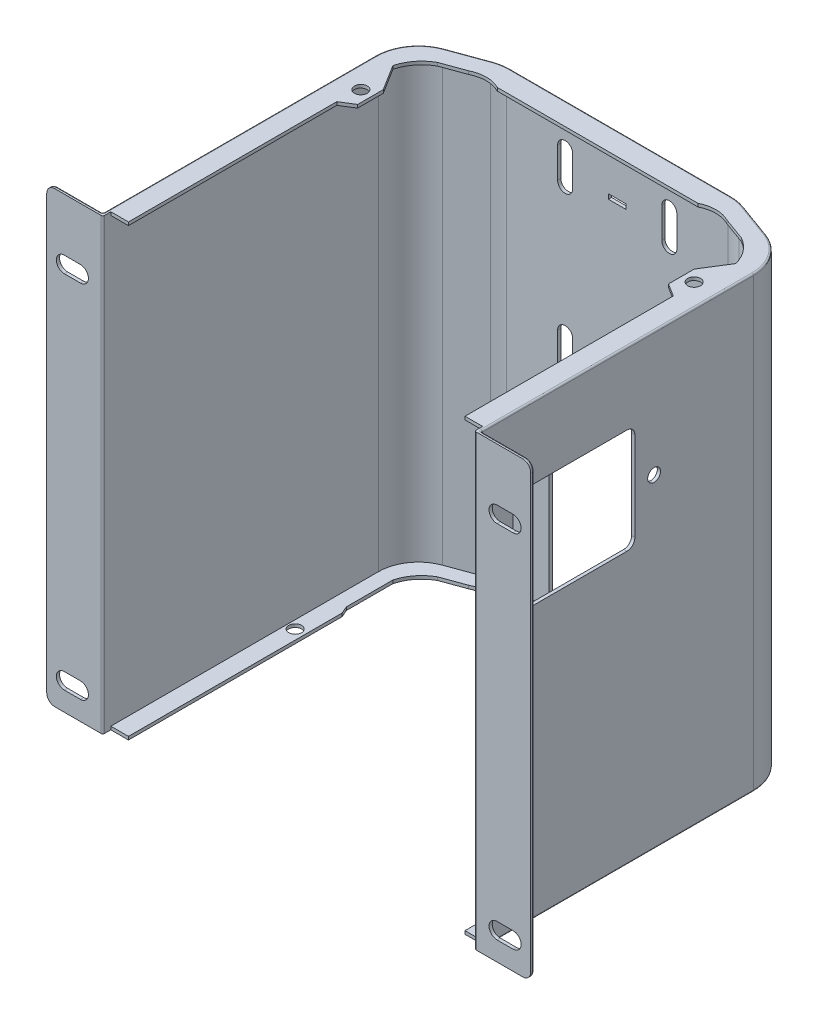
SolidWorks part; units mm, degrees
ref_plane "Front Plane" through (0, 0, 0) normal (0, 0, 1) x (1, 0, 0)
ref_plane "Top Plane" through (0, 0, 0) normal (0, 1, 0) x (1, 0, 0)
ref_plane "Right Plane" through (0, 0, 0) normal (1, 0, 0) x (0, 0, -1)
sketch "Sketch1" plane through (0, 0, 0) normal (0, 1, 0) x (1, 0, 0)
  line L0 (-72.524, 103.4923) -> (-94.5505, 95.4753)
  line L1 (-63.9735, 105) -> (73.9735, 105)
  line L2 (-111, 71.983) -> (-111, -99)
  line L4 (121, 71.983) -> (121, -99)
  line L5 (-109.326, 90.3521) -> (121, -100) construction
  line L6 (-111, -100) -> (111, 100) construction
  line L7 (82.524, 103.4923) -> (104.5505, 95.4753)
  line L8 (122, -100) -> (156, -100)
  line L9 (-112, -100) -> (-146, -100)
  line L10 (-114, -98) -> (-146, -98)
  line L11 (-113, 71.983) -> (-113, -97)
  line L12 (-73.208, 105.3717) -> (-95.2345, 97.3547)
  line L13 (-63.9735, 107) -> (73.9735, 107)
  line L14 (83.208, 105.3717) -> (105.2345, 97.3547)
  line L15 (123, 71.983) -> (123, -97)
  line L16 (124, -98) -> (156, -98)
  line L17 (-146, -98) -> (-146, -100)
  line L18 (156, -98) -> (156, -100)
  line L19 (-113, -98) -> (-146, -98) construction
  line L20 (-113, 71.983) -> (-113, -98) construction
  line L21 (-111, -100) -> (-146, -100) construction
  line L22 (-111, 71.983) -> (-111, -100) construction
  line L23 (123, -98) -> (156, -98) construction
  line L24 (123, 71.983) -> (123, -98) construction
  line L25 (121, -100) -> (156, -100) construction
  line L26 (121, 71.983) -> (121, -100) construction
  arc A0 (121, 71.983) -> (104.5505, 95.4753) centre (96, 71.983) ccw
  arc A1 (-111, 71.983) -> (-94.5505, 95.4753) centre (-86, 71.983) cw
  arc A2 (82.524, 103.4923) -> (73.9735, 105) centre (73.9735, 80) ccw
  arc A3 (-72.524, 103.4923) -> (-63.9735, 105) centre (-63.9735, 80) cw
  arc A4 (-113, 71.983) -> (-95.2345, 97.3547) centre (-86, 71.983) cw
  arc A5 (-73.208, 105.3717) -> (-63.9735, 107) centre (-63.9735, 80) cw
  arc A6 (83.208, 105.3717) -> (73.9735, 107) centre (73.9735, 80) ccw
  arc A7 (123, 71.983) -> (105.2345, 97.3547) centre (96, 71.983) ccw
  arc A8 (-114, -98) -> (-113, -97) centre (-114, -97) ccw
  arc A9 (-112, -100) -> (-111, -99) centre (-112, -99) ccw
  arc A10 (124, -98) -> (123, -97) centre (124, -97) cw
  arc A11 (122, -100) -> (121, -99) centre (122, -99) cw
  point P0 (0, 0)
  dimension "D1" = 25
  dimension "D2" = 25
  dimension "D8" = 1
  dimension "D3" = 35
  dimension "D4" = 35
  dimension "D5" = 20
  dimension "D6" = 20
  dimension "D7" = 2
extrude "Boss-Extrude1" add sketch "Sketch1" against normal blind 280
fillet "Fillet1" radius 5 4 edges at (156, 0, 99) (-146, 0, 99) (-146, -280, 99) (156, -280, 99)
sketch "Sketch2" plane through (0, -280, 0) normal (0, -1, 0) x (1, 0, 0)
  line L0 (-102, -47.983) -> (-102, -55.983)
  line L1 (5, -106) -> (5, -85.9828) construction
  line L2 (99.7633, -87.6401) -> (85.6679, -92.7704)
  line L3 (112, -55.983) -> (112, -71.983)
  line L4 (112, -47.983) -> (112, -55.983)
  line L5 (112, -42.983) -> (112, -47.983)
  line L6 (110, -38.3496) -> (112, -42.983)
  line L7 (110, 95) -> (110, -38.3496)
  line L8 (122, 95) -> (110, 95)
  line L25 (-112, 95) -> (-100, 95)
  line L26 (-100, 95) -> (-100, -38.3496)
  line L27 (-100, -38.3496) -> (-102, -42.983)
  line L28 (-102, -42.983) -> (-102, -47.983)
  line L30 (-102, -55.983) -> (-102, -71.983)
  line L31 (-89.7633, -87.6401) -> (-75.6679, -92.7704)
  line L32 (-57.5976, -92.7704) -> (67.5976, -92.7704)
  line L33 (-141, 100) -> (-112, 100) construction
  line L34 (-141, 99) -> (-146, 99)
  line L35 (156, 99) -> (151, 99)
  line L36 (151, 99) -> (122, 99)
  line L37 (122, 99) -> (122, -71.983)
  line L38 (104.8925, -96.415) -> (82.866, -104.432)
  line L39 (73.9735, -106) -> (-63.9735, -106)
  line L40 (-72.866, -104.432) -> (-94.8925, -96.415)
  line L41 (-112, 99) -> (-141, 99)
  line L42 (-112, -71.983) -> (-112, 99)
  line L44 (156, 99) -> (151, 99)
  line L45 (151, 99) -> (122, 99)
  line L46 (122, 99) -> (122, -71.983)
  line L47 (104.8925, -96.415) -> (82.866, -104.432)
  line L48 (73.9735, -106) -> (-63.9735, -106)
  line L49 (-72.866, -104.432) -> (-94.8925, -96.415)
  line L51 (-112, -71.983) -> (-112, 95)
  arc A0 (85.6679, -92.7704) -> (67.5976, -92.7704) centre (76.6328, -74.9276) cw
  arc A1 (112, -71.983) -> (99.7633, -87.6401) centre (87.8063, -65.6849) cw
  circle A2 centre (-106, -15) radius 4
  circle A3 centre (116, -15) radius 4
  arc A18 (-102, -71.983) -> (-89.7633, -87.6401) centre (-77.8063, -65.6849) ccw
  arc A19 (-75.6679, -92.7704) -> (-57.5976, -92.7704) centre (-66.6328, -74.9276) ccw
  arc A24 (104.8925, -96.415) -> (122, -71.983) centre (96, -71.983) ccw
  arc A25 (73.9735, -106) -> (82.866, -104.432) centre (73.9735, -80) ccw
  arc A26 (-72.866, -104.432) -> (-63.9735, -106) centre (-63.9735, -80) ccw
  arc A27 (-112, -71.983) -> (-94.8925, -96.415) centre (-86, -71.983) ccw
  arc A28 (104.8925, -96.415) -> (122, -71.983) centre (96, -71.983) ccw
  arc A29 (73.9735, -106) -> (82.866, -104.432) centre (73.9735, -80) ccw
  arc A30 (-72.866, -104.432) -> (-63.9735, -106) centre (-63.9735, -80) ccw
  arc A31 (-112, -71.983) -> (-94.8925, -96.415) centre (-86, -71.983) ccw
  line M42 (121, 99) -> (121, -71.983)
  arc M43 (121, -71.983) -> (104.5505, -95.4753) centre (96, -71.983) cw
  line M44 (104.5505, -95.4753) -> (82.524, -103.4923)
  arc M45 (82.524, -103.4923) -> (73.9735, -105) centre (73.9735, -80) cw
  line M46 (73.9735, -105) -> (-63.9735, -105)
  arc M47 (-63.9735, -105) -> (-72.524, -103.4923) centre (-63.9735, -80) cw
  line M48 (-72.524, -103.4923) -> (-94.5505, -95.4753)
  arc M49 (-94.5505, -95.4753) -> (-111, -71.983) centre (-86, -71.983) cw
  line M50 (-111, -71.983) -> (-111, 99)
  dimension "D5" = 10
  dimension "D6" = 25
  dimension "D7" = 20
  dimension "D11" = 8
  dimension "D12" = 110
  dimension "D13" = 6
  dimension "D2" = 5
  dimension "D3" = 12
  dimension "D4" = 10
  dimension "D8" = 5
  dimension "D9" = 8
  dimension "D10" = 16
  dimension "D14" = 15
  dimension "D15" = 10
  dimension "D1" = 1
extrude "Boss-Extrude2" add sketch "Sketch2" against normal blind 2 contours L1 L8 L7 L6 L5 L4 L3 A1 L2 A0 L32 A3 M46 M45 M44 M43 M42 | L1 L32 A19 L31 A18 L30 L0 L28 L27 L26 L25 A2 M46 M50 M49 M48 M47
ref_plane "Plane1" through (0, -140, 0) normal (0, 1, 0) x (1, 0, 0)
sketch "Sketch3" plane through (0, 0, 0) normal (0, 1, 0) x (1, 0, 0)
  line L0 (5, 92.7704) -> (5, 63.9915) construction
  line L1 (122, -95) -> (110, -95)
  line L2 (110, -95) -> (110, 35)
  line L3 (110, 35) -> (102, 40)
  line L4 (102, 40) -> (102, 56)
  line L5 (102, 56) -> (112, 71.983)
  line L6 (99.7633, 87.6401) -> (85.6679, 92.7704)
  line L14 (-112, -95) -> (-100, -95)
  line L15 (-100, -95) -> (-100, 35)
  line L16 (-100, 35) -> (-92, 40)
  line L17 (-92, 40) -> (-92, 56)
  line L18 (-92, 56) -> (-102, 71.983)
  line L19 (122, 71.983) -> (122, -99)
  line L20 (82.866, 104.432) -> (104.8925, 96.415)
  line L21 (-112, -99) -> (-112, 71.983)
  line L22 (-63.9735, 106) -> (73.9735, 106)
  line L23 (-94.8925, 96.415) -> (-72.866, 104.432)
  line L24 (122, 71.983) -> (122, -95)
  line L25 (82.866, 104.432) -> (104.8925, 96.415)
  line L26 (-112, -95) -> (-112, 71.983)
  line L27 (-63.9735, 106) -> (73.9735, 106)
  line L28 (-94.8925, 96.415) -> (-72.866, 104.432)
  line L30 (-89.7633, 87.6401) -> (-75.6679, 92.7704)
  line L31 (-141, -100) -> (-112, -100) construction
  line L32 (-57.5976, 92.7704) -> (67.5976, 92.7704)
  circle A0 centre (109, 49) radius 4
  arc A1 (112, 71.983) -> (99.7633, 87.6401) centre (87.8063, 65.6849) ccw
  arc A2 (85.6679, 92.7704) -> (67.5976, 92.7704) centre (76.6328, 74.9276) ccw
  arc A10 (-102, 71.983) -> (-89.7633, 87.6401) centre (-77.8063, 65.6849) cw
  arc A11 (-75.6679, 92.7704) -> (-57.5976, 92.7704) centre (-66.6328, 74.9276) cw
  arc A14 (122, 71.983) -> (104.8925, 96.415) centre (96, 71.983) ccw
  arc A15 (82.866, 104.432) -> (73.9735, 106) centre (73.9735, 80) ccw
  arc A16 (-63.9735, 106) -> (-72.866, 104.432) centre (-63.9735, 80) ccw
  arc A17 (-94.8925, 96.415) -> (-112, 71.983) centre (-86, 71.983) ccw
  arc A18 (122, 71.983) -> (104.8925, 96.415) centre (96, 71.983) ccw
  arc A19 (82.866, 104.432) -> (73.9735, 106) centre (73.9735, 80) ccw
  arc A20 (-63.9735, 106) -> (-72.866, 104.432) centre (-63.9735, 80) ccw
  arc A21 (-94.8925, 96.415) -> (-112, 71.983) centre (-86, 71.983) ccw
  circle A22 centre (-99, 49) radius 4
  point P31 (82.7156, 90.2053)
  dimension "D8" = 144
  dimension "D9" = 7
  dimension "D10" = 8
  dimension "D2" = 12
  dimension "D3" = 5
  dimension "D4" = 20
  dimension "D5" = 16
  dimension "D6" = 5
  dimension "D7" = 130
  dimension "D1" = 1
extrude "Boss-Extrude3" add sketch "Sketch3" against normal blind 2
fillet "Fillet3" radius 1 32 edges at (-84.2213, 0, -101.3632) (-68.662, 0, -106.5898) (5, 0, -107) (78.662, 0, -106.5898) (94.2213, 0, -101.3632) (118.1171, 0, -87.4696) (123, 0, 12.5085) (123.2929, 0, 97.7071) (137.5, 0, 98) (154.5355, -1.4645, 98) (156, -140, 98) (154.5355, -278.5355, 98) (137.5, -280, 98) (123.2929, -280, 97.7071) (123, -280, 12.5085) (118.1171, -280, -87.4696) (94.2213, -280, -101.3632) (78.662, -280, -106.5898) (5, -280, -107) (-68.662, -280, -106.5898) (-84.2213, -280, -101.3632) (-108.1171, 0, -87.4696) (-108.1171, -280, -87.4696) (-113, 0, 12.5085) (-113, -280, 12.5085) (-113.2929, 0, 97.7071) (-113.2929, -280, 97.7071) (-127.5, -280, 98) (-144.5355, -278.5355, 98) (-146, -140, 98) (-144.5355, -1.4645, 98) (-127.5, 0, 98)
sketch "Sketch6" plane through (0, 0, 98) normal (0, 0, -1) x (-1, 0, 0)
  line L0 (125, -38) -> (135, -38) construction
  line L1 (125, -33) -> (135, -33)
  line L2 (125, -43) -> (135, -43)
  line L3 (145, -275) -> (145, -5) construction
  line L4 (141, -1) -> (114, -1) construction
  line L5 (125, -263) -> (135, -263) construction
  line L6 (125, -258) -> (135, -258)
  line L7 (125, -268) -> (135, -268)
  line L8 (-5, -1) -> (-5, 16.278) construction
  line L9 (141, -1) -> (-151, -1) construction
  line L10 (-135, -38) -> (-145, -38) construction
  line L11 (-135, -33) -> (-145, -33)
  line L12 (-135, -43) -> (-145, -43)
  line L13 (-135, -263) -> (-145, -263) construction
  line L14 (-135, -258) -> (-145, -258)
  line L15 (-135, -268) -> (-145, -268)
  arc A0 (125, -33) -> (125, -43) centre (125, -38) ccw
  arc A1 (135, -43) -> (135, -33) centre (135, -38) ccw
  arc A2 (125, -258) -> (125, -268) centre (125, -263) ccw
  arc A3 (135, -268) -> (135, -258) centre (135, -263) ccw
  arc A4 (-135, -33) -> (-135, -43) centre (-135, -38) cw
  arc A5 (-145, -43) -> (-145, -33) centre (-145, -38) cw
  arc A6 (-135, -258) -> (-135, -268) centre (-135, -263) cw
  arc A7 (-145, -268) -> (-145, -258) centre (-145, -263) cw
  point P2 (130, -38)
  point P13 (130, -263)
  point P27 (-140, -38)
  point P34 (-140, -263)
  dimension "D1" = 5
  dimension "D3" = 10
  dimension "D5" = 5
  dimension "D7" = 10
  dimension "D2" = 10
  dimension "D4" = 32
  dimension "D6" = 10
  dimension "D8" = 215
extrude "Cut-Extrude3" cut sketch "Sketch6" along direction (0, 0, 1) on the side against the normal up to surface (2 mm away) contours L2 A1 L1 A0 | L7 A3 L6 A2 | A7 L15 A6 L14 | A5 L12 A4 L11
sketch "Sketch7" plane through (0, 0, -107) normal (0, 0, -1) x (-1, 0, 0)
  line L0 (-37.5, -24.5033) -> (-37.5, -43.5682) construction
  line L1 (-32.7898, -24.5033) -> (-32.7898, -43.5682)
  line L2 (-42.2102, -24.5033) -> (-42.2102, -43.5682)
  line L3 (27.5, -24.5033) -> (27.5, -43.5682) construction
  line L4 (32.2102, -24.5033) -> (32.2102, -43.5682)
  line L5 (22.7898, -24.5033) -> (22.7898, -43.5682)
  line L6 (27.5, -124.5033) -> (27.5, -143.5682) construction
  line L7 (32.2102, -124.5033) -> (32.2102, -143.5682)
  line L8 (22.7898, -124.5033) -> (22.7898, -143.5682)
  line L9 (-37.5, -124.5033) -> (-37.5, -143.5682) construction
  line L10 (-32.7898, -124.5033) -> (-32.7898, -143.5682)
  line L11 (-42.2102, -124.5033) -> (-42.2102, -143.5682)
  line L12 (-5, -1) -> (-5, -16.0632) construction
  line L13 (63.9735, -1) -> (-73.9735, -1) construction
  line L14 (-73.9735, -279) -> (63.9735, -279) construction
  line L15 (37.5, -376.5) -> (-47.5, -376.5)
  line L16 (37.5, -376.5) -> (37.5, -181.5)
  line L18 (-47.5, -376.5) -> (-47.5, -181.5)
  line L19 (37.5, -376.5) -> (-47.5, -181.5) construction
  line L20 (37.5, -181.5) -> (-47.5, -376.5) construction
  arc A0 (-32.7898, -24.5033) -> (-42.2102, -24.5033) centre (-37.5, -24.5033) ccw
  arc A1 (-42.2102, -43.5682) -> (-32.7898, -43.5682) centre (-37.5, -43.5682) ccw
  arc A2 (32.2102, -24.5033) -> (22.7898, -24.5033) centre (27.5, -24.5033) ccw
  arc A3 (22.7898, -43.5682) -> (32.2102, -43.5682) centre (27.5, -43.5682) ccw
  arc A4 (32.2102, -124.5033) -> (22.7898, -124.5033) centre (27.5, -124.5033) ccw
  arc A5 (22.7898, -143.5682) -> (32.2102, -143.5682) centre (27.5, -143.5682) ccw
  arc A6 (-32.7898, -124.5033) -> (-42.2102, -124.5033) centre (-37.5, -124.5033) ccw
  arc A7 (-42.2102, -143.5682) -> (-32.7898, -143.5682) centre (-37.5, -143.5682) ccw
  arc A8 (-47.5, -181.5) -> (37.5, -181.5) centre (-5, -181.5) cw
  point P2 (-37.5, -34.0358)
  point P12 (27.5, -34.0358)
  point P19 (27.5, -134.0358)
  point P26 (-37.5, -134.0358)
  point P32 (-5, -279)
  dimension "D3" = 32.5
  dimension "D4" = 85
  dimension "D1" = 2
  dimension "D2" = 2
extrude "Cut-Extrude4" cut sketch "Sketch7" against normal through all
sketch "Sketch8" plane through (0, 0, -107) normal (0, 0, -1) x (-1, 0, 0)
  line L1 (-10.5, -35) -> (0.5, -35)
  line L2 (-10.5, -35) -> (-10.5, -38)
  line L3 (-10.5, -38) -> (0.5, -38)
  line L4 (0.5, -35) -> (0.5, -38)
  line L5 (-73.9735, -1) -> (63.9735, -1) construction
  point P4 (-5, -35)
  point P10 (-5, -1)
  dimension "D1" = 11
  dimension "D2" = 3
  dimension "D3" = 35
extrude "Cut-Extrude5" cut sketch "Sketch8" against normal up to surface (2 mm away) up to face at (-27.5, -34.0358, -105)
sketch "Sketch9" plane through (123, 0, 0) normal (1, 0, 0) x (0, 0, -1)
  line L0 (-98, -5) -> (-98, -275) construction
  line L1 (-78, -45) -> (-2, -45)
  line L2 (-78, -45) -> (-78, -110.5)
  line L3 (-78, -110.5) -> (-2, -110.5)
  line L4 (-2, -45) -> (-2, -110.5)
  line L5 (-97, 0) -> (71.983, 0) construction
  circle A0 centre (10, -77.75) radius 4
  point P10 (-2, -77.75)
  dimension "D5" = 8
  dimension "D6" = 12
  dimension "D1" = 65.5
  dimension "D2" = 76
  dimension "D3" = 20
  dimension "D4" = 45
extrude "Cut-Extrude6" cut sketch "Sketch9" against normal up to surface (2 mm away) up to face at (121, -140, 54.2543)
fillet "Fillet4" radius 5 4 edges at (122, -45, 2) (122, -110.5, 2) (122, -110.5, 78) (122, -45, 78)
